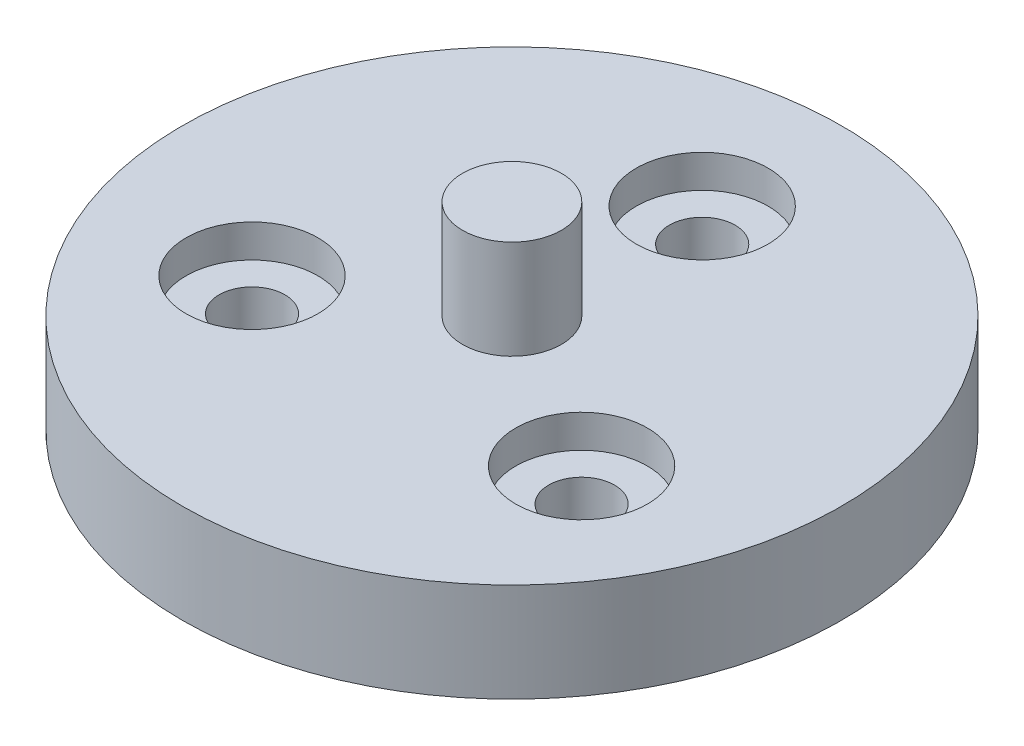
SolidWorks part; units mm, degrees
ref_plane "Front Plane" through (0, 0, 0) normal (0, 0, 1) x (1, 0, 0)
ref_plane "Top Plane" through (0, 0, 0) normal (0, 1, 0) x (1, 0, 0)
ref_plane "Right Plane" through (0, 0, 0) normal (1, 0, 0) x (0, 0, -1)
sketch "Sketch1" plane through (0, 0, 0) normal (0, 1, 0) x (1, 0, 0)
  line L1 (0, 5.7735) -> (-5, -2.8868) construction
  line L2 (-5, -2.8868) -> (5, -2.8868) construction
  line L3 (5, -2.8868) -> (0, 5.7735) construction
  circle A0 centre (0, 0) radius 10
  circle A1 centre (0, 0) radius 2.8868 construction
  circle A2 centre (0, 5.7735) radius 1
  circle A3 centre (-5, -2.8868) radius 1
  circle A4 centre (5, -2.8868) radius 1
extrude "Boss-Extrude1" add sketch "Sketch1" along normal blind 3
sketch "Sketch2" plane through (0, 3, 0) normal (0, 1, 0) x (1, 0, 0)
  circle A0 centre (0, 5.7735) radius 2
  circle A1 centre (-5, -2.8868) radius 2
  circle A2 centre (5, -2.8868) radius 2
extrude "Cut-Extrude1" cut sketch "Sketch2" against normal blind 1
sketch "Sketch3" plane through (0, 0, 0) normal (0, -1, 0) x (-1, 0, 0)
  circle A0 centre (0, 0) radius 4.5
extrude "Cut-Extrude2" [suppressed] cut sketch "Sketch3" against normal blind 1
sketch "Sketch4" plane through (0, 3, 0) normal (0, 1, 0) x (1, 0, 0)
  circle A0 centre (0, 0) radius 1.5
extrude "Boss-Extrude2" add sketch "Sketch4" along normal blind 3
